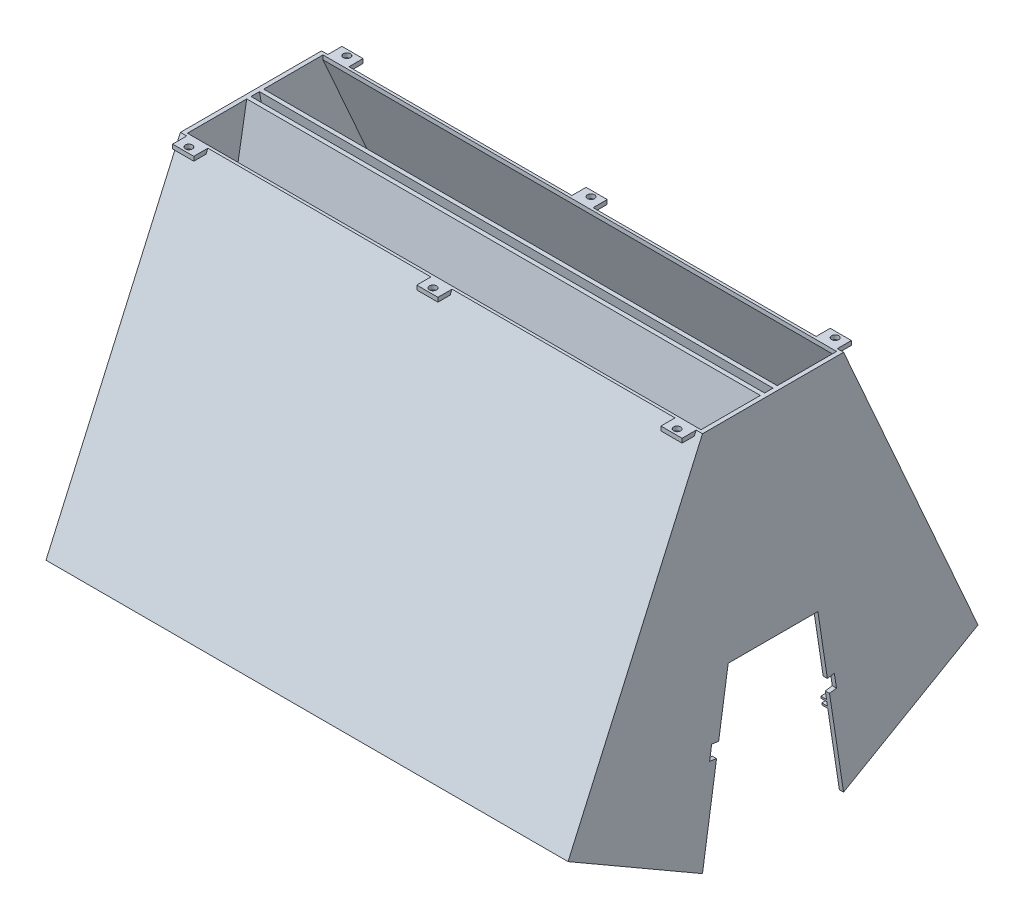
SolidWorks part; units mm, degrees
ref_plane "Front Plane" through (0, 0, 0) normal (0, 0, 1) x (1, 0, 0)
ref_plane "Top Plane" through (0, 0, 0) normal (0, 1, 0) x (1, 0, 0)
ref_plane "Right Plane" through (0, 0, 0) normal (1, 0, 0) x (0, 0, -1)
sketch "Sketch2" plane through (0, 0, 0) normal (1, 0, 0) x (0, 0, -1)
  line L1 (100, 0) -> (195.2628, 55)
  line L2 (0, 0) -> (-95.2628, 55)
  line L3 (81.7778, 120) -> (18.2222, 120)
  line L13 (0, 270) -> (-95.2628, 55)
  line L14 (0, 270) -> (100, 270)
  line L15 (100, 270) -> (195.2628, 55)
  line L16 (18.2222, 120) -> (0, 0)
  line L17 (100, 0) -> (81.7778, 120)
  dimension "D2" = 68.635
  dimension "D3" = 100
  dimension "D4" = 270
  dimension "D5" = 120
  dimension "D6" = 68.635
  dimension "D7" = 110
  dimension "D8" = 110
  dimension "D9" = 290.5256
  dimension "D10" = 100
extrude "Boss-Extrude1" add sketch "Sketch2" along normal blind 370
shell "Shell1" thickness 3
sketch "Sketch4" plane through (0, 267, 0) normal (0, -1, 0) x (1, 0, 0)
  line L5 (3, -1.952) -> (367, -1.952)
  line L6 (3, -1.952) -> (3, -98.048)
  line L7 (3, -98.048) -> (367, -98.048)
  line L8 (367, -1.952) -> (367, -98.048)
extrude "Cut-Extrude2" cut sketch "Sketch4" against normal through all
sketch "Sketch5" plane through (3, 0, 0) normal (1, 0, 0) x (0, 0, -1)
  line L1 (18.2222, 120) -> (81.7778, 120) construction
  line L2 (100, 270) -> (0, 270) construction
  line L3 (47, 270) -> (44, 270)
  line L4 (44, 270) -> (18.2222, 120)
  line L5 (18.2222, 120) -> (21.2222, 120)
  line L6 (21.2222, 120) -> (47, 270)
  line L7 (53, 270) -> (56, 270)
  line L8 (56, 270) -> (81.7778, 120)
  line L9 (81.7778, 120) -> (78.7778, 120)
  line L10 (78.7778, 120) -> (53, 270)
  dimension "D2" = 3
  dimension "D4" = 3
extrude "Boss-Extrude2" add sketch "Sketch5" along normal up to next
ref_plane "Plane1" through (0, 267, 0) normal (0, 1, 0) x (1, 0, 0)
sketch "Sketch9" plane through (0, 267, 0) normal (0, 1, 0) x (1, 0, 0)
  line L6 (365.535, 110) -> (350.535, 110)
  line L7 (350.535, 100) -> (350.535, 110)
  line L12 (192.502, 100) -> (177.502, 100)
  line L13 (192.502, 100) -> (192.502, 110)
  line L14 (192.502, 110) -> (177.502, 110)
  line L15 (177.502, 100) -> (177.502, 110)
  line L54 (350.535, 110) -> (365.535, 110)
  line L55 (350.535, 110) -> (350.535, 100)
  line L58 (370, 100) -> (0, 100) construction
  line L60 (365.535, 110) -> (365.535, 100)
  line L61 (365.535, 100) -> (350.535, 100)
  line L63 (19.465, 100) -> (4.465, 100)
  line L64 (365.535, 0) -> (350.535, 0)
  line L65 (365.535, -10) -> (365.535, 0)
  line L66 (4.465, 0) -> (19.465, 0)
  line L67 (350.535, -10) -> (350.535, 0)
  line L68 (350.535, -10) -> (365.535, -10)
  line L69 (177.502, 0) -> (177.502, -10)
  line L70 (192.502, -10) -> (177.502, -10)
  line L71 (192.502, 0) -> (192.502, -10)
  line L72 (192.502, 0) -> (177.502, 0)
  line L73 (19.465, 0) -> (19.465, -10)
  line L74 (4.465, -10) -> (19.465, -10)
  line L75 (350.535, 0) -> (350.535, -10)
  line L76 (365.535, -10) -> (350.535, -10)
  line L77 (4.465, -10) -> (4.465, 0)
  line L78 (19.465, 100) -> (19.465, 110)
  line L79 (19.465, 110) -> (4.465, 110)
  line L80 (4.465, 100) -> (4.465, 110)
  circle A6 centre (358.035, 106) radius 2.5
  circle A7 centre (185.002, 106) radius 2.5
  circle A17 centre (11.965, -6) radius 2.5
  circle A18 centre (185.002, -6) radius 2.5
  circle A19 centre (358.035, -6) radius 2.5
  circle A20 centre (11.965, 106) radius 2.5
  point P18 (11.965, 110)
  dimension "D9" = 5
  dimension "D10" = 5
  dimension "D5" = 4
  dimension "D4" = 5
  dimension "D2" = 15
  dimension "D3" = 10
  dimension "D6" = 15
  dimension "D7" = 10
  dimension "D8" = 158.037
extrude "Boss-Extrude4" add sketch "Sketch9" along normal blind 3 contours L80 L63 L78 L79 A20 | L15 L12 L13 L14 A7 | L61 L60 L6 L7 A6 | L67 L68 L65 L64 A19 | L71 L72 L69 L70 A18 | L77 L74 L73 L66 A17
sketch "Sketch10" plane through (3, 0, 0) normal (1, 0, 0) x (0, 0, -1)
  line L0 (9.1111, 60) -> (-91.7892, 62.8395)
  line L1 (0, 0) -> (18.2222, 120) construction
  line L2 (0, 270) -> (-95.2628, 55) construction
  line L3 (-91.7892, 62.8395) -> (-92.3969, 61.4681)
  line L4 (9.1111, 60) -> (8.8833, 58.5)
  line L5 (-92.3969, 61.4681) -> (8.8833, 58.5)
  line L8 (-93.7191, 58.4841) -> (8.4331, 55.5352)
  line L9 (8.4331, 55.5352) -> (8.2053, 54.0352)
  line L10 (8.2053, 54.0352) -> (-94.3837, 56.9841)
  line L11 (-94.3837, 56.9841) -> (-93.7191, 58.4841)
  line L12 (194.3837, 56.9841) -> (193.7191, 58.4841)
  line L13 (91.7947, 54.0352) -> (194.3837, 56.9841)
  line L14 (91.5669, 55.5352) -> (91.7947, 54.0352)
  line L15 (193.7191, 58.4841) -> (91.5669, 55.5352)
  line L16 (192.3969, 61.4681) -> (91.1167, 58.5)
  line L17 (90.8889, 60) -> (91.1167, 58.5)
  line L18 (191.7892, 62.8395) -> (192.3969, 61.4681)
  line L19 (90.8889, 60) -> (191.7892, 62.8395)
  dimension "D1" = 1.5
  dimension "D2" = 1.5
  dimension "D4" = 1.5
sketch "Sketch11" plane through (367, 0, 0) normal (-1, 0, 0) x (0, 0, 1)
  line L16 (-9.1111, 60) -> (-8.8833, 58.5)
  line L17 (-8.8833, 58.5) -> (92.3969, 61.4681)
  line L18 (92.3969, 61.4681) -> (91.7892, 62.8395)
  line L19 (91.7892, 62.8395) -> (-9.1111, 60)
  line L20 (94.3837, 56.9841) -> (93.7191, 58.4841)
  line L21 (93.7191, 58.4841) -> (-8.4331, 55.5352)
  line L22 (-8.4331, 55.5352) -> (-8.2053, 54.0352)
  line L23 (-8.2053, 54.0352) -> (94.3837, 56.9841)
  line L24 (-191.7892, 62.8395) -> (-90.8889, 60)
  line L25 (-90.8889, 60) -> (-91.1167, 58.5)
  line L26 (-91.1167, 58.5) -> (-192.3969, 61.4681)
  line L27 (-192.3969, 61.4681) -> (-191.7892, 62.8395)
  line L28 (-194.3837, 56.9841) -> (-193.7191, 58.4841)
  line L29 (-193.7191, 58.4841) -> (-91.5669, 55.5352)
  line L30 (-91.5669, 55.5352) -> (-91.7947, 54.0352)
  line L31 (-91.7947, 54.0352) -> (-194.3837, 56.9841)
extrude "Boss-Extrude5" add sketch "Sketch11" along normal blind 4
extrude "Boss-Extrude6" add sketch "Sketch10" along normal blind 4
sketch "Sketch12" plane through (370, 0, 0) normal (1, 0, 0) x (0, 0, -1)
  line L2 (11.4663, 75.51) -> (6.523, 76.2607)
  line L3 (0, 0) -> (18.2222, 120) construction
  line L4 (10.7157, 70.5667) -> (9.965, 65.6234)
  line L5 (9.965, 65.6234) -> (5.0217, 66.374)
  line L6 (5.0217, 66.374) -> (6.523, 76.2607)
  line L7 (10.7157, 70.5667) -> (11.4663, 75.51)
  line L8 (89.2843, 70.5667) -> (88.5337, 75.51)
  line L9 (94.9783, 66.374) -> (93.477, 76.2607)
  line L10 (90.035, 65.6234) -> (94.9783, 66.374)
  line L11 (89.2843, 70.5667) -> (90.035, 65.6234)
  line L12 (88.5337, 75.51) -> (93.477, 76.2607)
  dimension "D1" = 5
  dimension "D2" = 5
  dimension "D3" = 5
  dimension "D4" = 45
extrude "Cut-Extrude3" cut sketch "Sketch12" against normal through all
